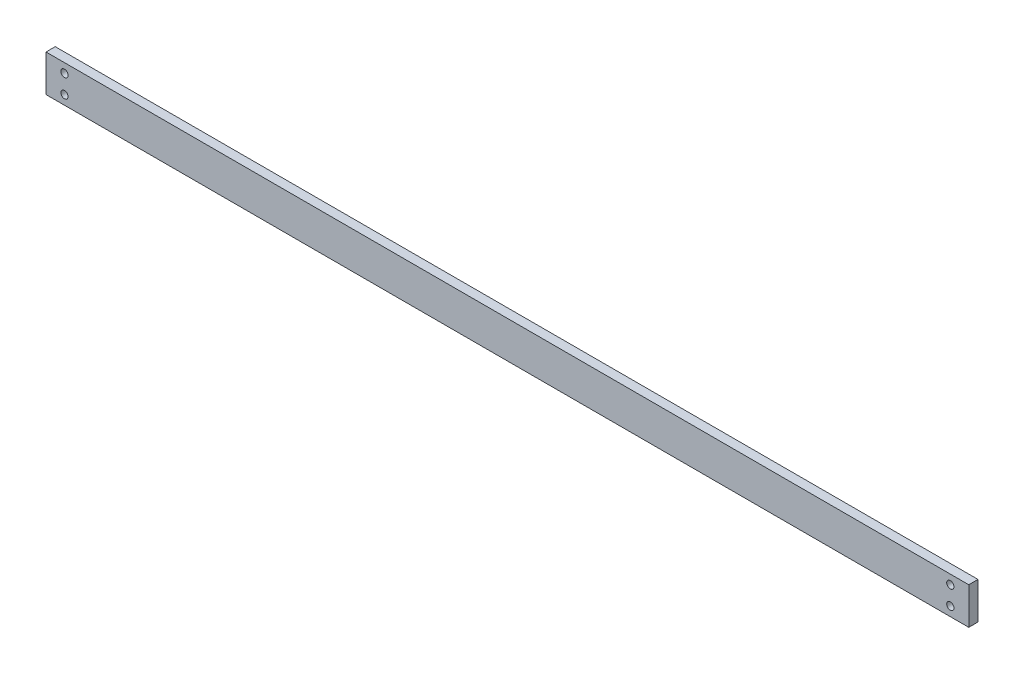
SolidWorks part; units mm, degrees
ref_plane "Front Plane" through (0, 0, 0) normal (0, 0, 1) x (1, 0, 0)
ref_plane "Top Plane" through (0, 0, 0) normal (0, 1, 0) x (1, 0, 0)
ref_plane "Right Plane" through (0, 0, 0) normal (1, 0, 0) x (0, 0, -1)
sketch "Sketch1" plane through (0, 0, 0) normal (0, 0, 1) x (1, 0, 0)
  line L1 (-317.5, -12.7) -> (317.5, -12.7)
  line L2 (-317.5, -12.7) -> (-317.5, 12.7)
  line L3 (-317.5, 12.7) -> (317.5, 12.7)
  line L4 (317.5, -12.7) -> (317.5, 12.7)
  line L5 (-317.5, -12.7) -> (317.5, 12.7) construction
  line L6 (-317.5, 12.7) -> (317.5, -12.7) construction
  point P0 (0, 0)
  dimension "D1" = 635
  dimension "D2" = 25.4
extrude "Boss-Extrude1" add sketch "Sketch1" along normal mid plane 6.35
sketch "Sketch2" plane through (0, 0, 0) normal (0, 0, 1) x (1, 0, 0)
  line L0 (317.5, -12.7) -> (317.5, 12.7) construction
  line L1 (317.5, 12.7) -> (-317.5, 12.7) construction
  line L2 (0, 12.7) -> (0, -12.7) construction
  line L3 (-317.5, -12.7) -> (317.5, -12.7) construction
  circle A0 centre (304.8, -6.35) radius 2.4892
  circle A1 centre (304.8, 6.35) radius 2.4892
  circle A4 centre (-304.8, 6.35) radius 2.4892
  circle A5 centre (-304.8, -6.35) radius 2.4892
  dimension "D2" = 4.9784
  dimension "D1" = 12.7
  dimension "D3" = 6.35
  dimension "D4" = 12.7
extrude "Cut-Extrude1" cut sketch "Sketch2" against normal through all both and the other way through all
